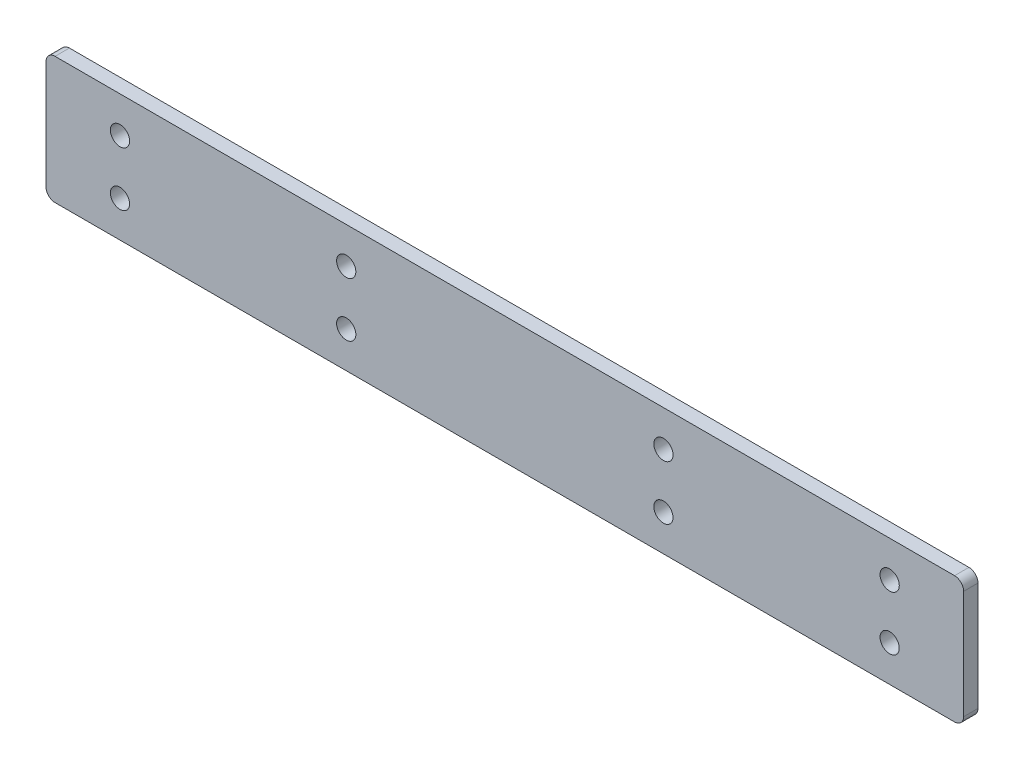
SolidWorks part; units mm, degrees
ref_plane "Front Plane" through (0, 0, 0) normal (0, 0, 1) x (1, 0, 0)
ref_plane "Top Plane" through (0, 0, 0) normal (0, 1, 0) x (1, 0, 0)
ref_plane "Right Plane" through (0, 0, 0) normal (1, 0, 0) x (0, 0, -1)
sketch "Sketch1" plane through (0, 0, 0) normal (0, 0, 1) x (1, 0, 0)
  line L0 (-101.4, 0) -> (101.4, 0) construction
  line L1 (-101.4, -14) -> (101.4, -14)
  line L2 (-101.4, -14) -> (-101.4, 14)
  line L3 (-101.4, 14) -> (101.4, 14)
  line L4 (101.4, -14) -> (101.4, 14)
  line L5 (-101.4, -14) -> (101.4, 14) construction
  line L6 (-101.4, 14) -> (101.4, -14) construction
  line L7 (0, 14) -> (0, -14) construction
  circle A0 centre (85.05, 6) radius 2.125
  circle A1 centre (85.05, -6) radius 2.125
  circle A2 centre (-85.05, -6) radius 2.125
  circle A3 centre (-85.05, 6) radius 2.125
  circle A4 centre (-35.05, 6) radius 2.125
  circle A5 centre (-35.05, -6) radius 2.125
  circle A6 centre (35.05, -6) radius 2.125
  circle A7 centre (35.05, 6) radius 2.125
  point P0 (0, 0)
  dimension "D2" = 4.25
  dimension "D5" = 4.25
  dimension "D1" = 202.8
  dimension "D3" = 6
  dimension "D4" = 8
  dimension "D6" = 50
  dimension "D7" = 16.35
extrude "Boss-Extrude1" add sketch "Sketch1" along normal blind 3.175
fillet "Fillet1" radius 2 4 edges at (101.4, -14, 1.5875) (101.4, 14, 1.5875) (-101.4, -14, 1.5875) (-101.4, 14, 1.5875)
